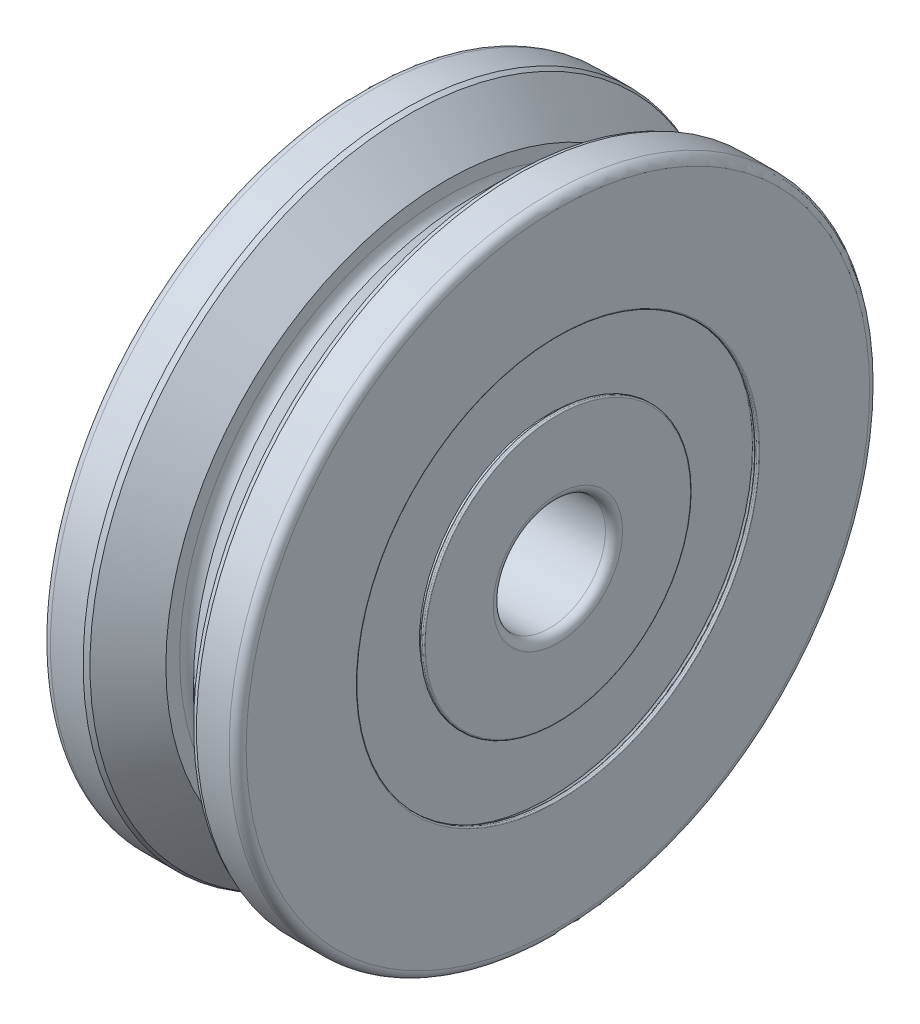
SolidWorks part; units mm, degrees
material "Plain Carbon Steel"
ref_plane "Front Plane" through (0, 0, 0) normal (0, 0, 1) x (1, 0, 0)
ref_plane "Top Plane" through (0, 0, 0) normal (0, 1, 0) x (1, 0, 0)
ref_plane "Right Plane" through (0, 0, 0) normal (1, 0, 0) x (0, 0, -1)
sketch "Sketch1" plane through (0, 0, 0) normal (0, 0, 1) x (1, 0, 0)
  line L0 (-6.9977, 9.4869) -> (-6.9977, 4.6228)
  line L1 (-6.3881, 4.0132) -> (6.3881, 4.0132)
  line L2 (6.9977, 4.6228) -> (6.9977, 9.4869)
  line L3 (6.8961, 9.5885) -> (6.7945, 9.5885)
  line L4 (6.6929, 9.4869) -> (6.6929, 9.2837)
  line L5 (6.6929, 9.2837) -> (6.3881, 9.2837)
  line L6 (6.3881, 9.2837) -> (6.3881, 14.5225)
  line L7 (6.4897, 14.624) -> (6.6929, 14.624)
  line L8 (6.6929, 14.624) -> (6.6929, 14.4208)
  line L9 (6.7945, 14.3193) -> (6.8961, 14.3193)
  line L10 (6.9977, 14.4208) -> (6.9977, 22.2885)
  line L11 (6.3881, 22.8981) -> (4.0509, 22.8981)
  line L12 (4.0509, 22.8981) -> (3.704, 22.7544)
  line L13 (3.704, 22.7544) -> (0.9906, 20.041)
  line L14 (0.9906, 20.041) -> (0.9906, 19.05)
  line L15 (-0.9906, 19.05) -> (-0.9906, 20.041)
  line L16 (-0.9906, 20.041) -> (-3.704, 22.7544)
  line L17 (-3.704, 22.7544) -> (-4.0509, 22.8981)
  line L18 (-4.0509, 22.8981) -> (-6.3881, 22.8981)
  line L19 (-6.9977, 22.2885) -> (-6.9977, 14.4208)
  line L20 (-6.8961, 14.3193) -> (-6.7945, 14.3193)
  line L21 (-6.6929, 14.4208) -> (-6.6929, 14.624)
  line L22 (-6.6929, 14.624) -> (-6.4897, 14.624)
  line L23 (-6.3881, 14.5225) -> (-6.3881, 9.2837)
  line L24 (-6.3881, 9.2837) -> (-6.6929, 9.2837)
  line L25 (-6.6929, 9.2837) -> (-6.6929, 9.4869)
  line L26 (-6.7945, 9.5885) -> (-6.8961, 9.5885)
  line L27 (-6.9977, 0) -> (6.9977, 0) construction
  arc A0 (-6.8961, 9.5885) -> (-6.9977, 9.4869) centre (-6.8961, 9.4869) ccw
  arc A1 (-6.9977, 4.6228) -> (-6.3881, 4.0132) centre (-6.3881, 4.6228) ccw
  arc A2 (6.3881, 4.0132) -> (6.9977, 4.6228) centre (6.3881, 4.6228) ccw
  arc A3 (6.9977, 9.4869) -> (6.8961, 9.5885) centre (6.8961, 9.4869) ccw
  arc A4 (6.7945, 9.5885) -> (6.6929, 9.4869) centre (6.7945, 9.4869) ccw
  arc A5 (6.3881, 14.5225) -> (6.4897, 14.624) centre (6.4897, 14.5224) cw
  arc A6 (6.6929, 14.4208) -> (6.7945, 14.3193) centre (6.7945, 14.4208) ccw
  arc A7 (6.8961, 14.3193) -> (6.9977, 14.4208) centre (6.8961, 14.4208) ccw
  arc A8 (6.9977, 22.2885) -> (6.3881, 22.8981) centre (6.3881, 22.2885) ccw
  arc A9 (0.9906, 19.05) -> (-0.9906, 19.05) centre (0, 19.05) cw
  arc A10 (-6.3881, 22.8981) -> (-6.9977, 22.2885) centre (-6.3881, 22.2885) ccw
  arc A11 (-6.9977, 14.4208) -> (-6.8961, 14.3193) centre (-6.8961, 14.4208) ccw
  arc A12 (-6.7945, 14.3193) -> (-6.6929, 14.4208) centre (-6.7945, 14.4208) ccw
  arc A13 (-6.4897, 14.624) -> (-6.3881, 14.5225) centre (-6.4897, 14.5225) cw
  arc A14 (-6.6929, 9.4869) -> (-6.7945, 9.5885) centre (-6.7945, 9.4869) ccw
revolve "Revolve1" add sketch "Sketch1" angle 360 about L27
